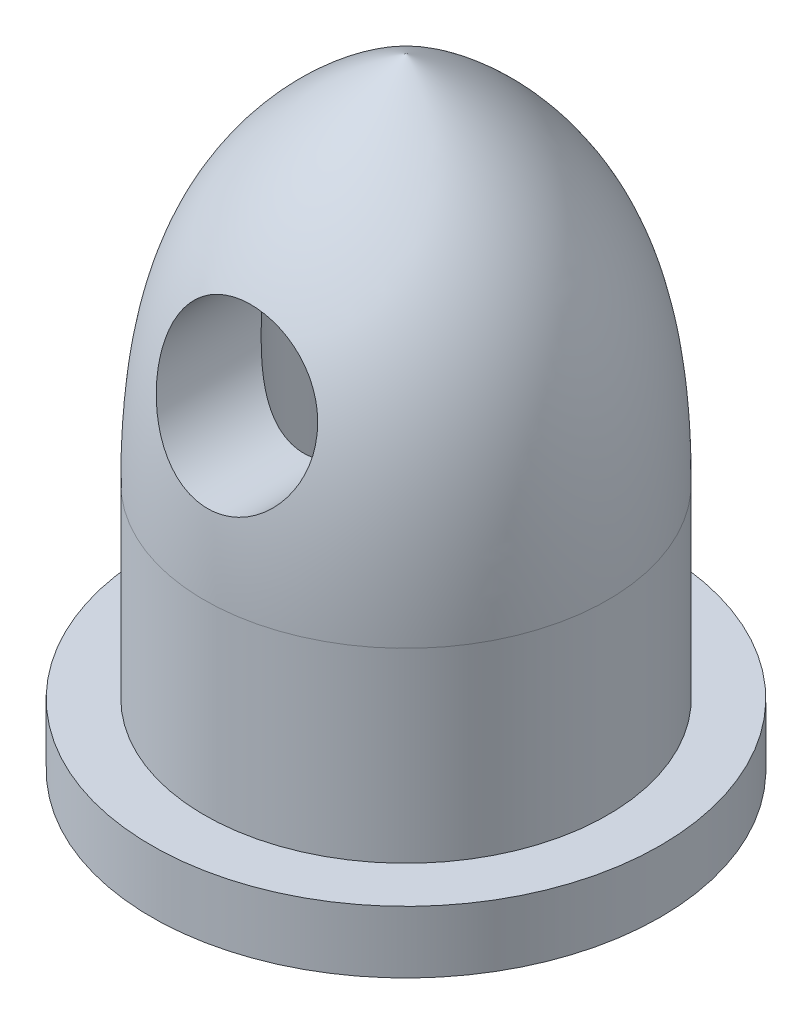
SolidWorks part; units mm, degrees
ref_plane "Front Plane" through (0, 0, 0) normal (0, 0, 1) x (1, 0, 0)
ref_plane "Top Plane" through (0, 0, 0) normal (0, 1, 0) x (1, 0, 0)
ref_plane "Right Plane" through (0, 0, 0) normal (1, 0, 0) x (0, 0, -1)
sketch "Sketch1" plane through (0, 0, 0) normal (0, 0, 1) x (1, 0, 0)
  line L0 (0, 0) -> (-4.1, 0)
  line L1 (-4.1, 0) -> (-4.1, 1)
  line L2 (-3.25, 1) -> (-3.25, 4)
  line L4 (0, 10) -> (0, 0)
  line L6 (-3.25, 1) -> (-4.1, 1)
  spline S0 degree 3 poles (-3.25, 4) (-3.25, 6.8097) (-2.5945, 8.6911) (0, 10) knots 0 0 0 0 1 1 1 1
  point P14 (-2.05, 0)
  dimension "D1" = 1
  dimension "D2" = 10
  dimension "D3" = 4.1
  dimension "D4" = 3.25
  dimension "D5" = 3
  dimension "D6" = 2.5
  dimension "D7" = 7.75
revolve "Revolve1" add sketch "Sketch1" angle 360 about L4
hole_wizard "M4x0.7 Tapped Hole1" positions "Sketch2" profile "Sketch3" tap size "M4x0.7" standard "ANSI Metric"
sketch "Sketch2" plane through (0, 0, 0) normal (0, -1, 0) x (-1, 0, 0)
  point P0 (0, 0)
sketch "Sketch3" plane through (0, 0, 0) normal (1, 0, 0) x (0, 0, -1)
  line L0 (0, 0) -> (0, 9.4914)
  line L1 (0, 9.4914) -> (1.65, 8.5)
  line L2 (1.65, 8.5) -> (1.65, 0)
  line L5 (1.65, 0) -> (0, 0)
  line L10 (0, 9.4914) -> (-1.65, 8.5) construction
  line L11 (0, -6.35) -> (0, 107.95) construction
  dimension "Tap Drill Dia." = 3.3
  dimension "Tap Drill Depth" = 8.5
  dimension "Drill Angle" = 118
cosmetic thread "Hole Thread1" parameters "D1"=8, "D2"=4
sketch "Sketch4" plane through (0, 0, 0) normal (0, 0, 1) x (1, 0, 0)
  line L0 (-4.1, 0) -> (4.1, 0) construction
  circle A0 centre (0, 6.5) radius 1.25
  dimension "D1" = 2.5
  dimension "D2" = 6.5
extrude "Cut-Extrude1" cut sketch "Sketch4" against normal through all both and the other way through all
